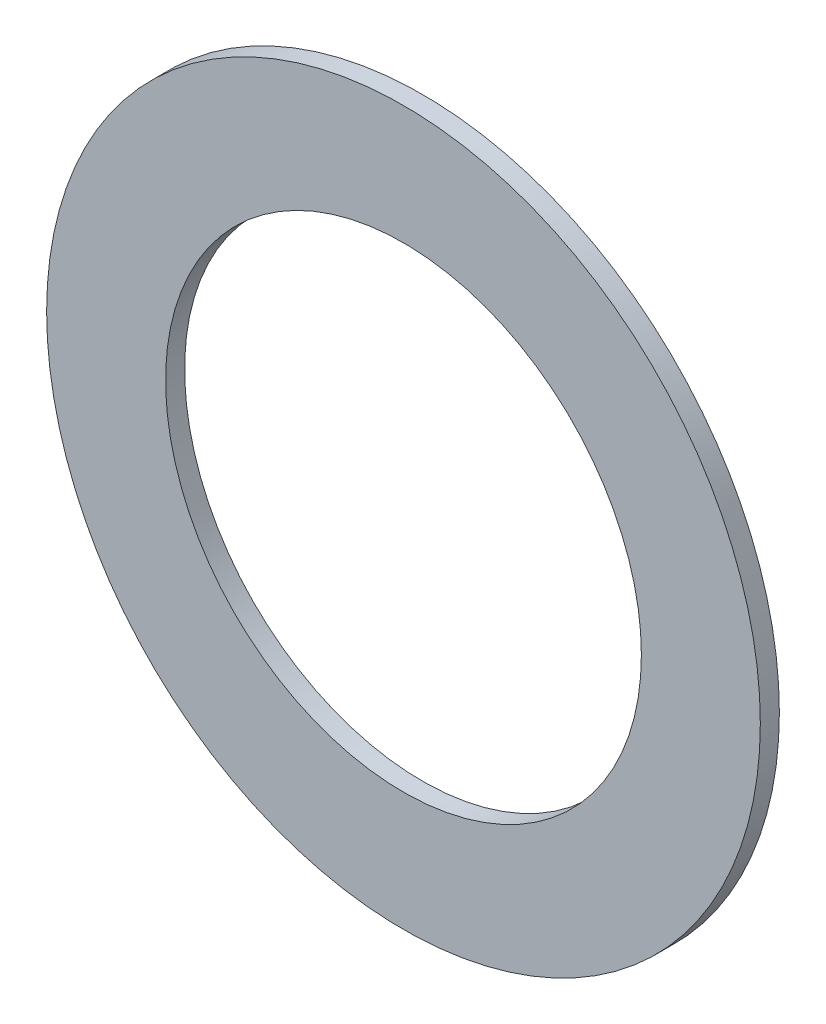
SolidWorks part; units mm, degrees
ref_plane "Front Plane" through (0, 0, 0) normal (0, 0, 1) x (1, 0, 0)
ref_plane "Top Plane" through (0, 0, 0) normal (0, 1, 0) x (1, 0, 0)
ref_plane "Right Plane" through (0, 0, 0) normal (1, 0, 0) x (0, 0, -1)
sketch "Sketch1" plane through (0, 0, 0) normal (0, 0, 1) x (1, 0, 0)
  circle A0 centre (0, 0) radius 3.175
  circle A1 centre (0, 0) radius 4.7625
  dimension "OD" = 9.525
  dimension "ID" = 6.35
sketch "Sketch2" plane through (0, 0, 0) normal (1, 0, 0) x (0, 0, -1)
  line L0 (-0.127, -4.7625) -> (0.127, -4.7625) construction
  line L1 (0, 4.7625) -> (0, -4.7625) construction
  point P3 (0, -4.7625)
sketch "Sketch3" plane through (0, 0, 0) normal (0, 0, 1) x (1, 0, 0)
  circle A0 centre (0, 0) radius 3.175 construction
  circle A1 centre (0, 0) radius 4.7625 construction
  circle A2 centre (0, 0) radius 3.175
  circle A3 centre (0, 0) radius 4.7625
extrude "Boss-Extrude1" add sketch "Sketch3" along normal mid plane 0.254
equation "\"D1@Boss-Extrude1\"=\"thickness@sketch2\""
